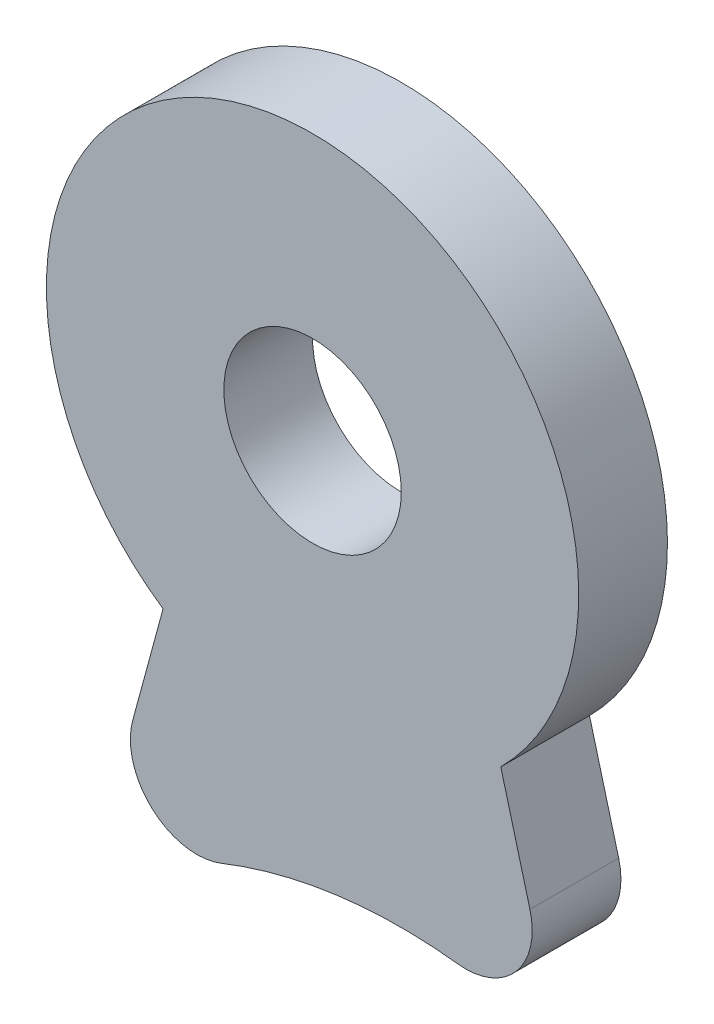
SolidWorks part; units mm, degrees
ref_plane "Front Plane" through (0, 0, 0) normal (0, 0, 1) x (1, 0, 0)
ref_plane "Top Plane" through (0, 0, 0) normal (0, 1, 0) x (1, 0, 0)
ref_plane "Right Plane" through (0, 0, 0) normal (1, 0, 0) x (0, 0, -1)
sketch "Sketch1" plane through (0, 0, 0) normal (0, 0, 1) x (1, 0, 0)
  line L0 (-177.7863, -30.1363) -> (-179.4321, -36.2)
  line L1 (-170.1736, -29.4148) -> (-168.876, -34.2574)
  circle A0 centre (-174.4163, -25.1722) radius 6
  arc A1 (-179.4321, -36.2) -> (-168.876, -34.2574) centre (-172.4163, -44.6722) cw
  circle A4 centre (-174.4163, -25.1722) radius 2
  point P7 (0, 0)
  point P8 (-174.4163, -25.1722)
  point P9 (0, 0)
  dimension "D2" = 12
  dimension "D1" = 4
  dimension "D3" = 11
  dimension "D4" = 168.876
  dimension "D5" = 170.1736
  dimension "D6" = 172.4163
  dimension "D7" = 177.7863
  dimension "D8" = 179.4321
  dimension "D9" = 34.2574
extrude "Boss-Extrude1" add sketch "Sketch1" along normal blind 2 contours A0 A4 | L0 A1 L1 A0
fillet "Fillet1" radius 1.5 2 edges at (-179.4321, -36.2, 1) (-168.876, -34.2574, 1)
